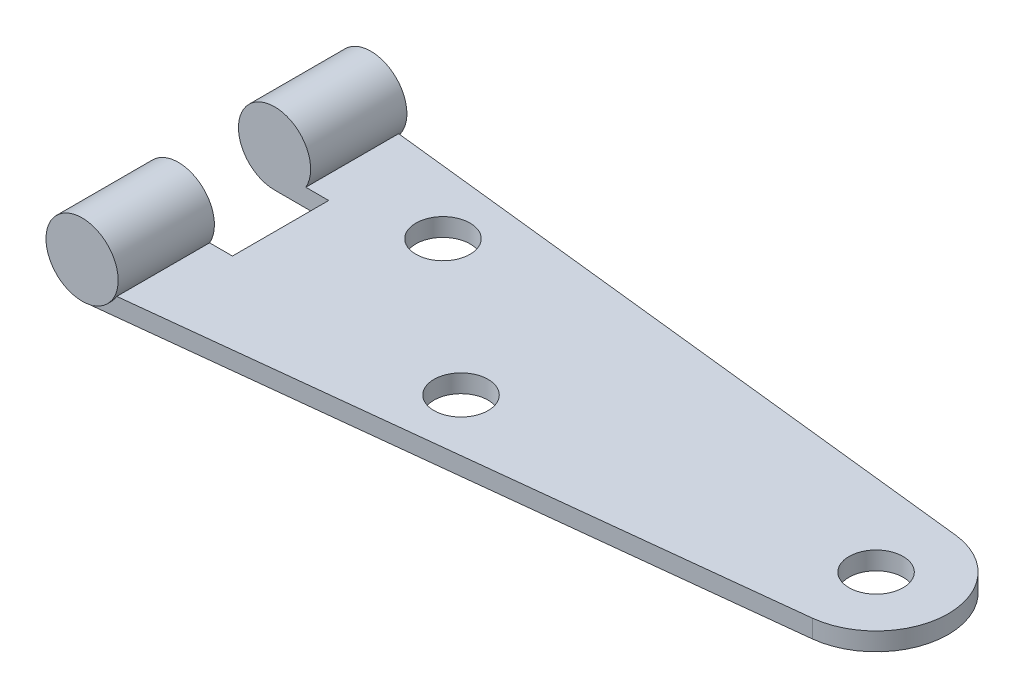
SolidWorks part; units mm, degrees
ref_plane "Front Plane" through (0, 0, 0) normal (0, 0, 1) x (1, 0, 0)
ref_plane "Top Plane" through (0, 0, 0) normal (0, 1, 0) x (1, 0, 0)
ref_plane "Right Plane" through (0, 0, 0) normal (1, 0, 0) x (0, 0, -1)
sketch "Sketch1" plane through (0, 0, 0) normal (0, 1, 0) x (1, 0, 0)
  line L0 (-57.15, 12.7) -> (-57.15, -12.7)
  line L1 (-57.15, 12.7) -> (0.697, 6.3116)
  line L2 (-57.15, -12.7) -> (0.697, -6.3116)
  arc A0 (0.697, -6.3116) -> (0.697, 6.3116) centre (0, 0) ccw
  circle A1 centre (0, 0) radius 2.3813
  circle A2 centre (-44.45, 6.35) radius 2.3812
  circle A3 centre (-31.75, -4.7625) radius 2.3812
  point P5 (-6.35, 0)
  point P6 (-57.15, 0)
  dimension "D1" = 25.4
  dimension "D3" = 12.7
  dimension "D4" = 4.7625
  dimension "D5" = 6.35
  dimension "D6" = 4.7625
  dimension "D8" = 4.7625
  dimension "D2" = 50.8
  dimension "D7" = 12.7
  dimension "D9" = 25.4
  dimension "D10" = 7.9375
extrude "Boss-Extrude1" add sketch "Sketch1" along normal blind 1.5875
sketch "Sketch2" plane through (-57.15, 0, 0) normal (-1, 0, 0) x (0, 0, 1)
  line L0 (-12.7, 3.175) -> (12.7, 3.175) construction
  line L1 (-12.7, 0) -> (12.7, 0) construction
  line L3 (-12.7, 3.175) -> (12.7, 3.175)
  line L4 (-12.7, 3.175) -> (-12.7, 0)
  line L5 (-12.7, 0) -> (12.7, 0)
  line L6 (12.7, 3.175) -> (12.7, 0)
  dimension "D1" = 3.175
revolve "Revolve1" add sketch "Sketch2" angle 360 about L0
sketch "Sketch3" plane through (0, 1.5875, 0) normal (0, 1, 0) x (1, 0, 0)
  line L0 (-60.325, 12.7) -> (-60.325, -12.7) construction
  line L1 (-52.3875, 4.2333) -> (-60.325, 4.2333)
  line L2 (-52.3875, 4.2333) -> (-52.3875, -4.2333)
  line L3 (-52.3875, -4.2333) -> (-60.325, -4.2333)
  line L4 (-60.325, 4.2333) -> (-60.325, -4.2333)
  line L5 (-53.975, 12.7) -> (-60.325, 12.7) construction
  dimension "D1" = 8.4667
  dimension "D2" = 8.4667
  dimension "D3" = 7.9375
extrude "Cut-Extrude1" cut sketch "Sketch3" against normal through all and the other way through all
